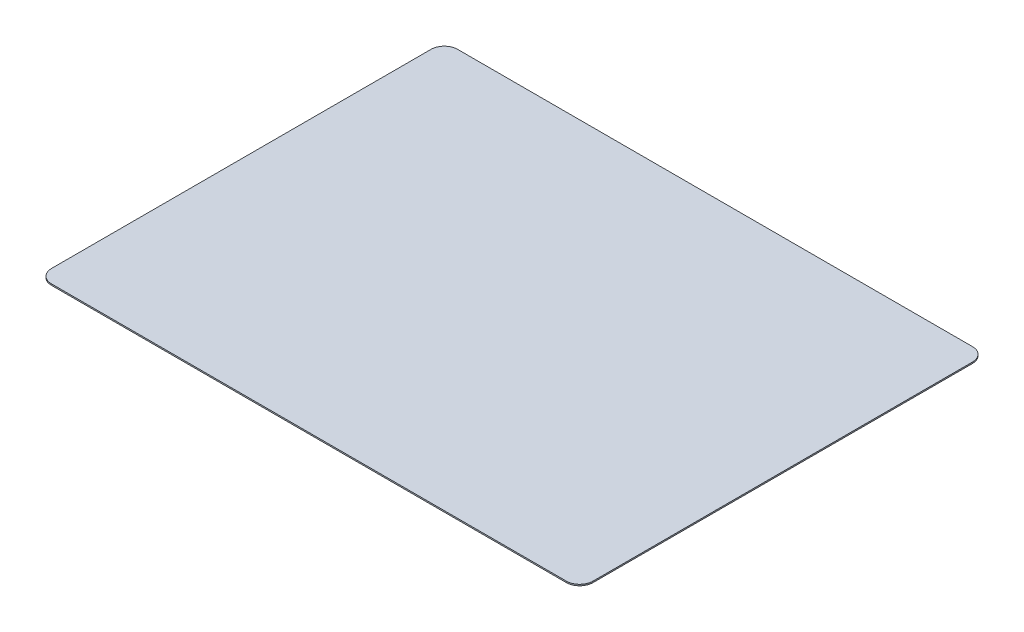
SolidWorks part; units mm, degrees
ref_plane "Front Plane" through (0, 0, 0) normal (0, 0, 1) x (1, 0, 0)
ref_plane "Top Plane" through (0, 0, 0) normal (0, 1, 0) x (1, 0, 0)
ref_plane "Right Plane" through (0, 0, 0) normal (1, 0, 0) x (0, 0, -1)
sketch "Sketch1" plane through (0, 0, 0) normal (0, 1, 0) x (1, 0, 0)
  line L1 (-203.2, 152.4) -> (203.2, 152.4)
  line L2 (-203.2, 152.4) -> (-203.2, -152.4)
  line L3 (-203.2, -152.4) -> (203.2, -152.4)
  line L4 (203.2, 152.4) -> (203.2, -152.4)
  line L5 (-203.2, 152.4) -> (203.2, -152.4) construction
  line L6 (-203.2, -152.4) -> (203.2, 152.4) construction
  point P0 (0, 0)
  dimension "D1" = 406.4
  dimension "D2" = 304.8
extrude "Boss-Extrude1" add sketch "Sketch1" along normal blind 1
fillet "Fillet1" radius 10 4 edges at (203.2, 0.5, -152.4) (-203.2, 0.5, -152.4) (-203.2, 0.5, 152.4) (203.2, 0.5, 152.4)
